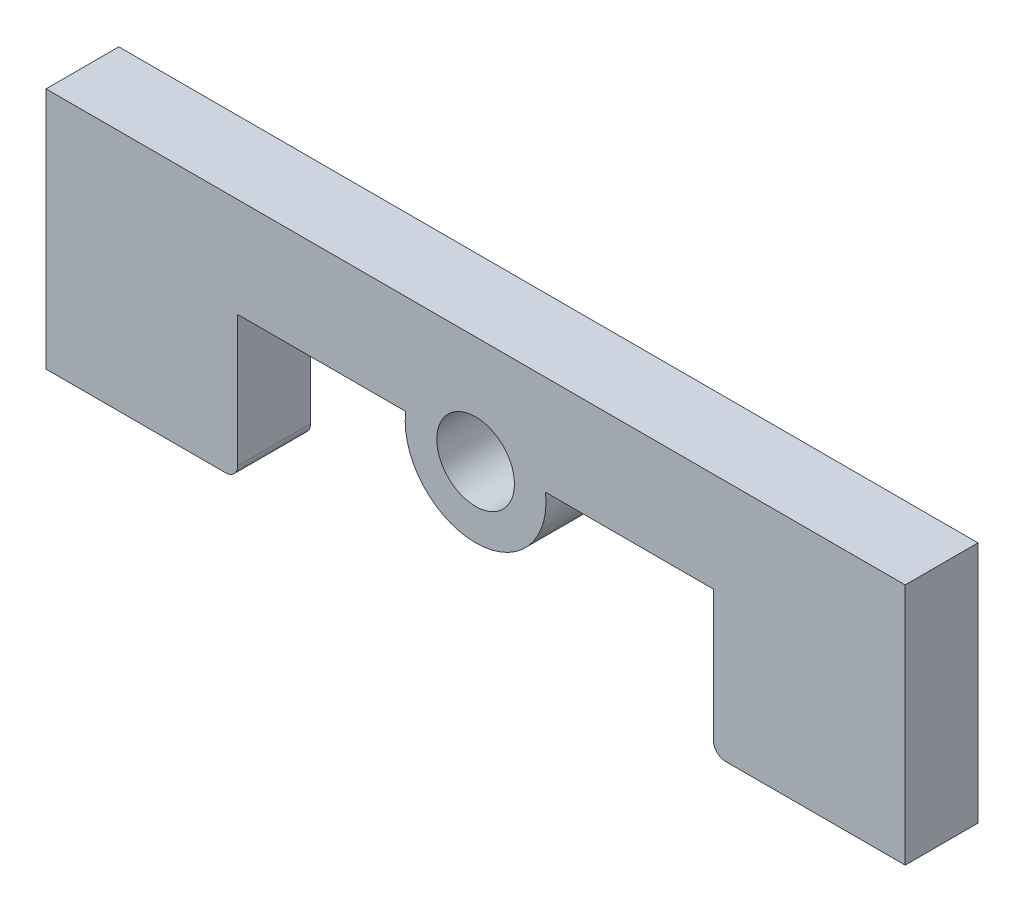
SolidWorks part; units mm, degrees
ref_plane "Front Plane" through (0, 0, 0) normal (0, 0, 1) x (1, 0, 0)
ref_plane "Top Plane" through (0, 0, 0) normal (0, 1, 0) x (1, 0, 0)
ref_plane "Right Plane" through (0, 0, 0) normal (1, 0, 0) x (0, 0, -1)
sketch "Sketch2" plane through (0, 0, 0) normal (0, 0, 1) x (1, 0, 0)
  line L0 (9.8, -5) -> (17.7, -5)
  line L1 (-17.7, -5) -> (-9.8, -5)
  line L2 (-17.7, -5) -> (-17.7, 5)
  line L3 (-17.7, 5) -> (17.7, 5)
  line L4 (17.7, -5) -> (17.7, 5)
  line L5 (-17.7, -5) -> (17.7, 5) construction
  line L6 (-17.7, 5) -> (17.7, -5) construction
  line L8 (-9.8, -5) -> (-9.8, 0.9)
  line L9 (-9.8, 0.9) -> (9.8, 0.9)
  line L10 (9.8, -5) -> (9.8, 0.9)
  circle A0 centre (0, 0.55) radius 1.6
  circle A1 centre (0, 0.55) radius 2.9
  point P0 (0, 0)
  dimension "D3" = 3.2
  dimension "D4" = 4.45
  dimension "D8" = 17.7
  dimension "D9" = 5.8
  dimension "D10" = 4.45
  dimension "D1" = 10
  dimension "D2" = 35.4
  dimension "D5" = 5.9
  dimension "D6" = 19.6
  dimension "D7" = 7.9
extrude "Boss-Extrude2" add sketch "Sketch2" along normal blind 3 contours L9 A1 A0 | A1 L9 L10 L0 L4 L3 L2 L1 L8 | L9 A1 A0
fillet "Fillet1" radius 2.5 2 edges at (-6.3394, 0.9, 0) (6.3394, 0.9, 0)
fillet "Fillet2" radius 0.5 2 edges at (9.8, -5, 1.5) (-9.8, -5, 1.5)
